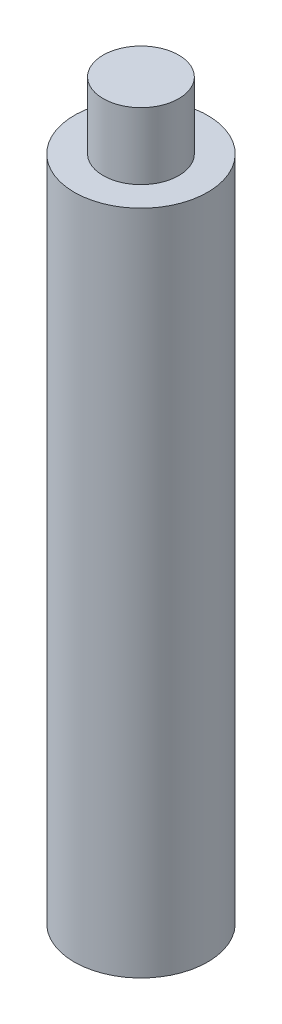
SolidWorks part; units mm, degrees
ref_plane "Front Plane" through (0, 0, 0) normal (0, 0, 1) x (1, 0, 0)
ref_plane "Top Plane" through (0, 0, 0) normal (0, 1, 0) x (1, 0, 0)
ref_plane "Right Plane" through (0, 0, 0) normal (1, 0, 0) x (0, 0, -1)
sketch "Sketch1" plane through (-72.684, -103.0986, -8.6975) normal (0, 1, 0) x (0.999, 0, 0.0438)
  circle A0 centre (18.3113, 0.7621) radius 3
  circle A1 centre (18.3113, 0.7621) radius 1.7
  dimension "D1" = 3.4
  dimension "D2" = 6
extrude "Boss-Extrude1" add sketch "Sketch1" along normal blind 30 from offset 3
sketch "Sketch2" plane through (0, -70.0986, 0) normal (0, 1, 0) x (1, 0, 0)
  circle A0 centre (-54.3568, 8.6568) radius 1.7
extrude "Boss-Extrude2" add sketch "Sketch2" along normal blind 3 separate body
